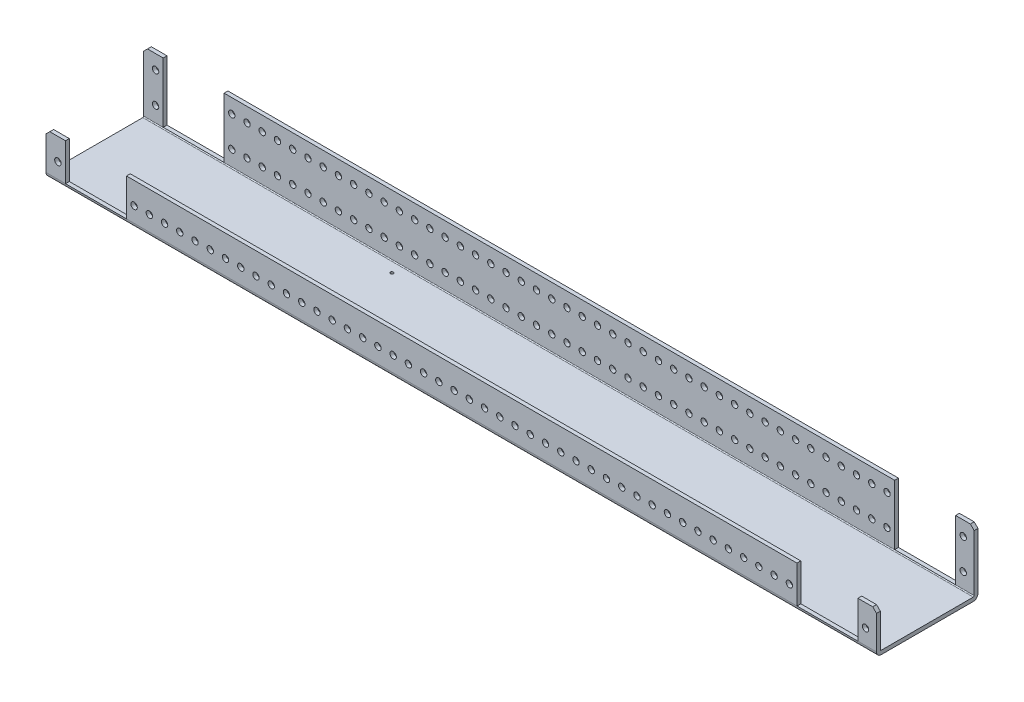
SolidWorks part; units mm, degrees
ref_plane "Front Plane" through (0, 0, 0) normal (0, 0, 1) x (1, 0, 0)
ref_plane "Top Plane" through (0, 0, 0) normal (0, 1, 0) x (1, 0, 0)
ref_plane "Right Plane" through (0, 0, 0) normal (1, 0, 0) x (0, 0, -1)
ref_plane "Plane1" through (0, 53.975, 0) normal (0, 1, 0) x (1, 0, 0)
sketch "Sketch1" plane through (0, 53.975, 0) normal (0, 1, 0) x (1, 0, 0)
  line L0 (692.15, 84.582) -> (0, 84.582)
  line L1 (0, 84.582) -> (0, 0)
  line L2 (0, 0) -> (692.15, 0)
  line L3 (692.15, 0) -> (692.15, 84.582)
  dimension "D1" = 692.15
  dimension "D2" = 84.582
extrude "Boss-Extrude1" add sketch "Sketch1" against normal blind 53.975
sketch "Sketch2" plane through (692.15, 0, 0) normal (1, 0, 0) x (0, 0, -1)
  line L0 (-3.175, 3.175) -> (81.407, 3.175)
  line L1 (81.407, 3.175) -> (81.407, 53.975)
  line L2 (81.407, 53.975) -> (-3.175, 53.975)
  line L3 (-3.175, 53.975) -> (-3.175, 3.175)
  line L4 (0, 0) -> (84.582, 0) construction
  line L5 (84.582, 0) -> (84.582, 53.975) construction
  line L6 (0, 53.975) -> (84.582, 53.975) construction
  dimension "D1" = 3.175
  dimension "D2" = 3.175
extrude "Cut-Extrude1" cut sketch "Sketch2" against normal through all
sketch "Sketch3" plane through (0, 3.175, 0) normal (0, 1, 0) x (-1, 0, 0)
  line L0 (0, -3.175) -> (-692.15, -3.175)
  line L1 (-692.15, -3.175) -> (-692.15, 0)
  line L2 (-692.15, 0) -> (0, 0)
  line L3 (0, 0) -> (0, -3.175)
  line L4 (-692.15, 0) -> (-692.15, -81.407) construction
  line L5 (0, 0) -> (-692.15, 0) construction
  line L6 (0, 0) -> (0, -81.407) construction
  dimension "D1" = 3.175
extrude "Boss-Extrude2" add sketch "Sketch3" along normal blind 31.75
hole_wizard "M2 Clearance Hole1" positions "Sketch5" profile "Sketch4" hole size "M2" standard "ANSI Metric"
sketch "Sketch5" plane through (0, 3.175, 0) normal (0, 1, 0) x (1, 0, 0)
  point P1 (215.9, 5.842)
  point P2 (215.9, 72.39)
  dimension "D1" = 215.9
  dimension "D2" = 5.842
  dimension "D3" = 66.548
sketch "Sketch4" plane through (215.9, 3.175, -5.842) normal (1, 0, 0) x (0, 0, 1)
  line L0 (0, 0) -> (0, 3.175)
  line L1 (0, 3.175) -> (1.27, 3.175)
  line L2 (1.27, 3.175) -> (1.27, 0)
  line L5 (1.27, 0) -> (0, 0)
  line L11 (0, -6.35) -> (0, 107.95) construction
  dimension "Thru Hole Dia." = 2.54
  dimension "Thru Hole Depth" = 3.175
hole_wizard "M5 Clearance Hole2" positions "Sketch9" profile "Sketch8" hole size "M5" standard "ANSI Metric" end condition through all
sketch "Sketch9" plane through (0, 0, -84.582) normal (0, 0, -1) x (-1, 0, 0)
  point P63 (2.794, 16.637)
  point P133 (-9.906, 16.637)
  point P134 (-22.606, 16.637)
  point P135 (-35.306, 16.637)
  point P136 (-48.006, 16.637)
  point P137 (-60.706, 16.637)
  point P138 (-73.406, 16.637)
  point P139 (-86.106, 16.637)
  point P140 (-98.806, 16.637)
  point P141 (-111.506, 16.637)
  point P142 (-9.906, 42.037)
  point P143 (-22.606, 42.037)
  point P144 (-35.306, 42.037)
  point P145 (-48.006, 42.037)
  point P146 (-60.706, 42.037)
  point P147 (-73.406, 42.037)
  point P148 (-86.106, 42.037)
  point P149 (-98.806, 42.037)
  point P150 (-111.506, 42.037)
  point P151 (2.794, 42.037)
  point P157 (-124.206, 16.637)
  point P158 (-136.906, 16.637)
  point P159 (-149.606, 16.637)
  point P160 (-162.306, 16.637)
  point P161 (-175.006, 16.637)
  point P162 (-187.706, 16.637)
  point P163 (-200.406, 16.637)
  point P164 (-213.106, 16.637)
  point P165 (-225.806, 16.637)
  point P166 (-238.506, 16.637)
  point P167 (-251.206, 16.637)
  point P168 (-263.906, 16.637)
  point P169 (-276.606, 16.637)
  point P170 (-289.306, 16.637)
  point P171 (-302.006, 16.637)
  point P172 (-314.706, 16.637)
  point P173 (-327.406, 16.637)
  point P174 (-340.106, 16.637)
  point P175 (-352.806, 16.637)
  point P176 (-365.506, 16.637)
  point P177 (-378.206, 16.637)
  point P178 (-390.906, 16.637)
  point P179 (-403.606, 16.637)
  point P180 (-416.306, 16.637)
  point P181 (-429.006, 16.637)
  point P182 (-441.706, 16.637)
  point P183 (-454.406, 16.637)
  point P184 (-467.106, 16.637)
  point P185 (-479.806, 16.637)
  point P186 (-492.506, 16.637)
  point P187 (-505.206, 16.637)
  point P188 (-517.906, 16.637)
  point P189 (-530.606, 16.637)
  point P190 (-543.306, 16.637)
  point P191 (-556.006, 16.637)
  point P192 (-568.706, 16.637)
  point P193 (-581.406, 16.637)
  point P194 (-594.106, 16.637)
  point P195 (-606.806, 16.637)
  point P196 (-619.506, 16.637)
  point P197 (-632.206, 16.637)
  point P198 (-644.906, 16.637)
  point P199 (-657.606, 16.637)
  point P200 (-670.306, 16.637)
  point P201 (-683.006, 16.637)
  point P202 (-695.706, 16.637)
  point P203 (-708.406, 16.637)
  point P204 (-721.106, 16.637)
  point P205 (-124.206, 42.037)
  point P206 (-136.906, 42.037)
  point P207 (-149.606, 42.037)
  point P208 (-162.306, 42.037)
  point P209 (-175.006, 42.037)
  point P210 (-187.706, 42.037)
  point P211 (-200.406, 42.037)
  point P212 (-213.106, 42.037)
  point P213 (-225.806, 42.037)
  point P214 (-238.506, 42.037)
  point P215 (-251.206, 42.037)
  point P216 (-263.906, 42.037)
  point P217 (-276.606, 42.037)
  point P218 (-289.306, 42.037)
  point P219 (-302.006, 42.037)
  point P220 (-314.706, 42.037)
  point P221 (-327.406, 42.037)
  point P222 (-340.106, 42.037)
  point P223 (-352.806, 42.037)
  point P224 (-365.506, 42.037)
  point P225 (-378.206, 42.037)
  point P226 (-390.906, 42.037)
  point P227 (-403.606, 42.037)
  point P228 (-416.306, 42.037)
  point P229 (-429.006, 42.037)
  point P230 (-441.706, 42.037)
  point P231 (-454.406, 42.037)
  point P232 (-467.106, 42.037)
  point P233 (-479.806, 42.037)
  point P234 (-492.506, 42.037)
  point P235 (-505.206, 42.037)
  point P236 (-517.906, 42.037)
  point P237 (-530.606, 42.037)
  point P238 (-543.306, 42.037)
  point P239 (-556.006, 42.037)
  point P240 (-568.706, 42.037)
  point P241 (-581.406, 42.037)
  point P242 (-594.106, 42.037)
  point P243 (-606.806, 42.037)
  point P244 (-619.506, 42.037)
  point P245 (-632.206, 42.037)
  point P246 (-644.906, 42.037)
  point P247 (-657.606, 42.037)
  point P248 (-670.306, 42.037)
  point P249 (-683.006, 42.037)
  point P250 (-695.706, 42.037)
  point P251 (-708.406, 42.037)
  point P252 (-721.106, 42.037)
  dimension "D1" = 16.637
  dimension "D2" = 2.794
  dimension "D3" = 58
  dimension "D4" = 2
sketch "Sketch8" plane through (-2.794, 16.637, -84.582) normal (1, 0, 0) x (0, 1, 0)
  line L0 (0, 0) -> (0, 84.582)
  line L1 (0, 84.582) -> (2.667, 84.582)
  line L2 (2.667, 84.582) -> (2.667, 0)
  line L5 (2.667, 0) -> (0, 0)
  line L11 (0, -6.35) -> (0, 107.95) construction
  dimension "Thru Hole Dia." = 5.334
  dimension "Thru Hole Depth" = 84.582
chamfer "Chamfer1" distance 3.175 angle 45 4 edges at (692.15, 53.975, -82.9945) (0, 34.925, -1.5875) (0, 53.975, -82.9945) (692.15, 34.925, -1.5875)
fillet "Fillet1" radius 0.762 2 edges at (346.075, 3.175, -3.175) (346.075, 3.175, -81.407)
fillet "Fillet2" radius 3.937 2 edges at (346.075, 0, -84.582) (346.075, 0, 0)
sketch "Sketch15" plane through (0, 0, -84.582) normal (0, 0, -1) x (-1, 0, 0)
  line L0 (0, 3.937) -> (0, 50.8) construction
  line L2 (-16.256, 27.686) -> (-16.256, 53.975)
  line L3 (-688.975, 53.975) -> (-3.175, 53.975) construction
  line L4 (-16.256, 53.975) -> (-67.056, 53.975)
  line L5 (-67.056, 53.975) -> (-67.056, 3.937)
  line L6 (-692.15, 3.937) -> (0, 3.937) construction
  line L7 (-67.056, 3.937) -> (-16.256, 3.937)
  line L8 (-16.256, 3.937) -> (-16.256, 27.686)
  dimension "D1" = 50.8
  dimension "D2" = 16.256
extrude "Cut-Extrude7" cut sketch "Sketch15" against normal blind 182.626 and the other way blind 58.674
sketch "Sketch16" plane through (0, 0, -84.582) normal (0, 0, -1) x (-1, 0, 0)
  line L0 (-692.15, 3.937) -> (-692.15, 50.8) construction
  line L2 (-676.656, 27.3685) -> (-676.656, 3.937)
  line L3 (-692.15, 3.937) -> (-67.056, 3.937) construction
  line L4 (-676.656, 3.937) -> (-625.856, 3.937)
  line L5 (-625.856, 3.937) -> (-625.856, 53.975)
  line L6 (-688.975, 53.975) -> (-67.056, 53.975) construction
  line L7 (-625.856, 53.975) -> (-676.656, 53.975)
  line L8 (-676.656, 53.975) -> (-676.656, 27.3685)
  dimension "D1" = 50.8
  dimension "D2" = 15.494
extrude "Cut-Extrude8" cut sketch "Sketch16" against normal blind 191.516 and the other way blind 66.802
